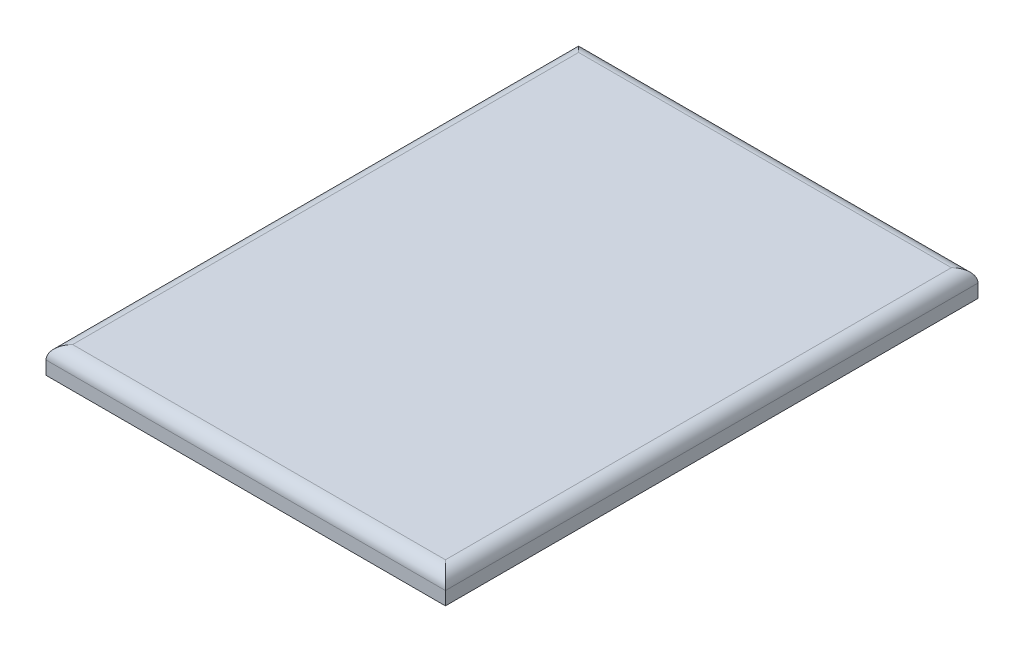
SolidWorks part; units mm, degrees
ref_plane "Front Plane" through (0, 0, 0) normal (0, 0, 1) x (1, 0, 0)
ref_plane "Top Plane" through (0, 0, 0) normal (0, 1, 0) x (1, 0, 0)
ref_plane "Right Plane" through (0, 0, 0) normal (1, 0, 0) x (0, 0, -1)
sketch "Sketch1" plane through (0, 0, 0) normal (0, 1, 0) x (1, 0, 0)
  line L1 (1.7785, 11.3758) -> (16.7785, 11.3758)
  line L2 (1.7785, 11.3758) -> (1.7785, -8.6242)
  line L3 (1.7785, -8.6242) -> (16.7785, -8.6242)
  line L4 (16.7785, 11.3758) -> (16.7785, -8.6242)
  dimension "D1" = 20
  dimension "D2" = 15
extrude "Boss-Extrude1" add sketch "Sketch1" along normal blind 1
fillet "Fillet1" radius 0.5 4 edges at (9.2785, 1, 8.6242) (1.7785, 1, -1.3758) (9.2785, 1, -11.3758) (16.7785, 1, -1.3758)
